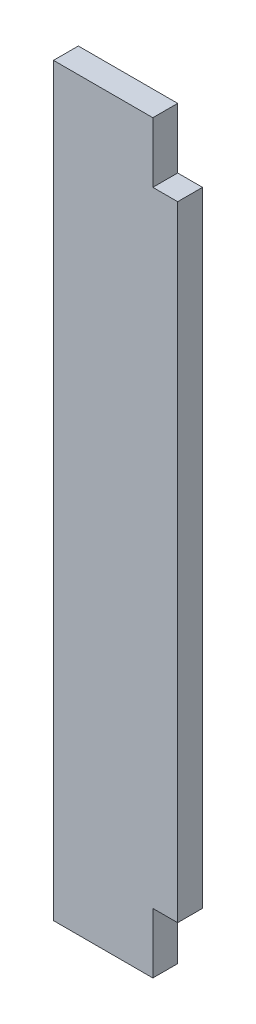
SolidWorks part; units mm, degrees
material "Pine"
ref_plane "Front Plane" through (0, 0, 0) normal (0, 0, 1) x (1, 0, 0)
ref_plane "Top Plane" through (0, 0, 0) normal (0, 1, 0) x (1, 0, 0)
ref_plane "Right Plane" through (0, 0, 0) normal (1, 0, 0) x (0, 0, -1)
sketch "Sketch1" plane through (0, 0, 0) normal (0, 0, 1) x (1, 0, 0)
  line L0 (8932.6508, -5243.5125) -> (10226.1458, -5243.5125)
  line L1 (9086.3208, -4722.0918) -> (10222.9708, -4853.7812)
  line L2 (8914.8708, -6342.0625) -> (10197.5708, -6342.0625)
  line L3 (8914.8708, -5808.6625) -> (10197.5708, -5808.6625)
  line L4 (8919.6333, -5253.0375) -> (10218.2083, -5253.0375)
  line L5 (9134.2633, -4656.1375) -> (9134.2633, -4638.3575)
  line L6 (9091.0833, -4638.3575) -> (9134.2633, -4638.3575)
  line L7 (9091.0833, -4567.2375) -> (9091.0833, -4638.3575)
  line L8 (9134.2633, -4656.1375) -> (9581.3033, -4656.1375)
  line L9 (9091.0833, -4567.2375) -> (9624.4833, -4567.2375)
  line L10 (9581.3033, -4656.1375) -> (9581.3033, -4638.3575)
  line L11 (9581.3033, -4638.3575) -> (9624.4833, -4638.3575)
  line L12 (9624.4833, -4567.2375) -> (9624.4833, -4638.3575)
  line L13 (8932.6508, -5225.7325) -> (9344.9775, -5225.7325)
  line L14 (8932.6508, -5256.2125) -> (8932.6508, -5243.5125)
  line L15 (8911.6958, -5256.2125) -> (8932.6508, -5256.2125)
  line L16 (8914.8708, -4722.0918) -> (9086.3208, -4722.0918)
  line L17 (8911.6958, -4715.5913) -> (8932.6508, -4715.5913)
  line L18 (8914.8708, -6342.0625) -> (8914.8708, -5808.6625)
  line L19 (12082.9917, -4722.0918) -> (10946.3417, -4853.7812)
  line L20 (12236.6617, -5243.5125) -> (10943.1667, -5243.5125)
  line L21 (10951.1042, -5253.0375) -> (12249.6792, -5253.0375)
  line L22 (10838.3917, -5656.2625) -> (11308.2917, -5656.2625)
  line L23 (10838.3917, -5719.7625) -> (11308.2917, -5719.7625)
  line L24 (10838.3917, -5742.5368) -> (11308.2917, -5742.5368)
  line L25 (10806.6417, -6342.0625) -> (11340.0417, -6342.0625)
  line L26 (10803.4667, -6335.7125) -> (11343.2167, -6335.7125)
  line L27 (10803.4667, -6317.9325) -> (11343.2167, -6317.9325)
  line L28 (10943.1667, -5225.7325) -> (11376.4483, -5225.7325)
  line L29 (11506.7292, -4754.5625) -> (10806.6417, -4827.5875)
  line L30 (11506.7292, -4567.2375) -> (11506.7292, -4754.5625)
  line L31 (10806.6417, -4567.2375) -> (10806.6417, -4827.5875)
  line L32 (10806.6417, -4567.2375) -> (11506.7292, -4567.2375)
  line L33 (10235.6708, -6329.3625) -> (10245.1958, -6329.3625)
  line L34 (10245.1958, -6329.3625) -> (10254.7208, -6278.5625)
  line L35 (10302.3458, -6329.3625) -> (10311.8708, -6278.5625)
  line L36 (10302.3458, -6329.3625) -> (10292.8208, -6329.3625)
  line L37 (10245.1958, -5821.3625) -> (10254.7208, -5872.1625)
  line L38 (10235.6708, -5821.3625) -> (10245.1958, -5821.3625)
  line L39 (10292.8208, -5821.3625) -> (10302.3458, -5821.3625)
  line L40 (10302.3458, -5821.3625) -> (10311.8708, -5872.1625)
  line L41 (10235.6708, -5821.3625) -> (10235.6708, -6329.3625)
  line L42 (10254.7208, -5872.1625) -> (10254.7208, -6278.5625)
  line L43 (10311.8708, -5872.1625) -> (10311.8708, -6278.5625)
  line L44 (10292.8208, -5821.3625) -> (10292.8208, -6329.3625)
  line L45 (8932.6508, -5225.7325) -> (8932.6508, -4715.5913)
  line L46 (8911.6958, -4715.5913) -> (8911.6958, -5256.2125)
  line L47 (8914.8708, -5248.275) -> (8914.8708, -4722.0918)
  line L48 (8919.6333, -5253.0375) -> (8914.8708, -5248.275)
  line L49 (8914.8708, -5145.0875) -> (8937.426, -5145.0875)
  line L50 (8914.8708, -5202.2375) -> (8937.426, -5202.2375)
  line L51 (10838.3917, -5656.2625) -> (10838.3917, -5719.7625)
  line L52 (10832.0417, -5736.1868) -> (10856.1717, -5736.1868)
  line L53 (10806.6417, -6342.0625) -> (10806.6417, -5818.7368)
  line L54 (10832.0417, -5649.9125) -> (10856.1717, -5649.9125)
  line L55 (10832.0417, -5726.1125) -> (10856.1717, -5726.1125)
  line L56 (10806.6417, -5818.7368) -> (10833.9015, -5818.7368)
  line L57 (10832.0417, -5806.0442) -> (10851.6815, -5806.0442)
  line L58 (10856.1717, -5801.5541) -> (10856.1717, -5736.1868)
  line L59 (10838.3917, -5814.2467) -> (10838.3917, -5742.5368)
  line L60 (10832.0417, -5806.0442) -> (10832.0417, -5736.1868)
  line L61 (10803.4667, -6317.9325) -> (10803.4667, -6335.7125)
  line L62 (10197.5708, -5808.6625) -> (10197.5708, -6342.0625)
  line L63 (9762.3842, -6348.4125) -> (9762.3842, -5802.3125)
  line L64 (9780.1642, -6348.4125) -> (9762.3842, -6348.4125)
  line L65 (9780.1642, -5802.3125) -> (9780.1642, -6348.4125)
  line L66 (9762.3842, -5802.3125) -> (9780.1642, -5802.3125)
  line L67 (9332.2775, -6348.4125) -> (9332.2775, -5802.3125)
  line L68 (9332.2775, -6348.4125) -> (9350.0575, -6348.4125)
  line L69 (9350.0575, -5802.3125) -> (9350.0575, -6348.4125)
  line L70 (9332.2775, -5802.3125) -> (9350.0575, -5802.3125)
  line L71 (9993.8374, -6061.075) -> (9993.8374, -6045.2418)
  line L72 (9998.5999, -6065.8375) -> (10014.4331, -6065.8375)
  line L73 (9998.5999, -6084.8875) -> (10014.4331, -6084.8875)
  line L74 (9993.8374, -6105.4832) -> (9993.8374, -6089.65)
  line L75 (9974.7874, -6105.4832) -> (9974.7874, -6089.65)
  line L76 (9954.1917, -6084.8875) -> (9970.0249, -6084.8875)
  line L77 (9974.7874, -6061.075) -> (9974.7874, -6045.2418)
  line L78 (9954.1917, -6065.8375) -> (9970.0249, -6065.8375)
  line L79 (10793.9417, -6237.2875) -> (10816.4969, -6237.2875)
  line L80 (10793.9417, -6294.4375) -> (10816.4969, -6294.4375)
  line L81 (10856.1717, -5649.9125) -> (10856.1717, -5726.1125)
  line L82 (10832.0417, -5726.1125) -> (10832.0417, -5649.9125)
  line L83 (10226.1458, -5225.7325) -> (10226.1458, -5243.5125)
  line L84 (10205.1908, -5257.8) -> (10205.1908, -4844.2499)
  line L85 (10230.9083, -4844.2499) -> (10230.9083, -5257.8)
  line L86 (10205.1908, -5257.8) -> (10230.9083, -5257.8)
  line L87 (10205.1908, -4844.2499) -> (10230.9083, -4844.2499)
  line L88 (10946.3417, -5176.8375) -> (10968.8969, -5176.8375)
  line L89 (9349.4676, -5141.9125) -> (9358.2674, -5141.9125)
  line L90 (10946.3417, -5119.6875) -> (10968.8969, -5119.6875)
  line L91 (9929.011, -4660.9635) -> (10066.0807, -4660.9635)
  line L92 (9929.011, -4678.7435) -> (10066.0807, -4678.7435)
  line L93 (10943.1667, -5225.7325) -> (10943.1667, -5243.5125)
  line L94 (10946.3417, -5248.275) -> (10951.1042, -5253.0375)
  line L95 (10946.3417, -5257.8063) -> (10946.3417, -4849.0188)
  line L96 (10964.1217, -5257.8) -> (10964.1217, -4844.2499)
  line L97 (10938.4042, -4844.2499) -> (10938.4042, -5257.8)
  line L98 (10938.4042, -5257.8) -> (10964.1217, -5257.8)
  line L99 (10964.1217, -4844.2499) -> (10938.4042, -4844.2499)
  line L100 (10344.8908, -4560.8875) -> (10369.0208, -4560.8875)
  line L101 (10344.8908, -4560.8875) -> (10369.0208, -4560.8875)
  line L102 (10800.2917, -4560.8875) -> (10824.4217, -4560.8875)
  line L103 (10200.4156, -5119.6875) -> (10222.9708, -5119.6875)
  line L104 (10200.4156, -5176.8375) -> (10222.9708, -5176.8375)
  line L105 (9344.9775, -5146.4026) -> (9344.9775, -5225.7325)
  line L106 (10344.8908, -4560.8875) -> (10344.8908, -4833.9375)
  line L107 (9792.8642, -5225.7325) -> (9792.8642, -5146.4026)
  line L108 (9362.7575, -5225.7325) -> (9775.0842, -5225.7325)
  line L109 (9680.3633, -4761.8396) -> (9680.3633, -4559.9604)
  line L110 (9656.2333, -4559.9604) -> (9680.3633, -4559.9604)
  line L111 (9656.2333, -4761.8396) -> (9680.3633, -4761.8396)
  line L112 (9656.2333, -4761.8396) -> (9656.2333, -4559.9604)
  line L113 (9779.5743, -5141.9125) -> (9788.374, -5141.9125)
  line L114 (10070.5708, -4665.4536) -> (10070.5708, -4674.2534)
  line L115 (9924.5208, -4674.2534) -> (9924.5208, -4665.4536)
  line L116 (12127.4417, -6188.3925) -> (12205.5015, -6188.3925)
  line L117 (12209.9917, -6170.6125) -> (12209.9917, -6183.9024)
  line L118 (9792.8642, -5225.7325) -> (10226.1458, -5225.7325)
  line L119 (9662.5833, -4754.5625) -> (10362.6708, -4827.5875)
  line L120 (9662.5833, -4567.2375) -> (9662.5833, -4754.5625)
  line L121 (10362.6708, -4567.2375) -> (10362.6708, -4827.5875)
  line L122 (9662.5833, -4567.2375) -> (10362.6708, -4567.2375)
  line L123 (10824.4217, -4833.9375) -> (10800.2917, -4833.9375)
  line L124 (10800.2917, -4833.9375) -> (10800.2917, -4560.8875)
  line L125 (10824.4217, -4560.8875) -> (10824.4217, -4833.9375)
  line L126 (10344.8908, -4833.9375) -> (10369.0208, -4833.9375)
  line L127 (10369.0208, -4833.9375) -> (10369.0208, -4560.8875)
  line L128 (10222.9708, -5248.275) -> (10218.2083, -5253.0375)
  line L129 (10222.9708, -5257.8063) -> (10222.9708, -4849.0188)
  line L130 (11734.6544, -5701.375) -> (11739.2301, -5701.375)
  line L131 (9362.7575, -5225.7325) -> (9362.7575, -5146.4026)
  line L132 (9775.0842, -5146.4026) -> (9775.0842, -5225.7325)
  line L133 (11761.3864, -5701.375) -> (11756.8282, -5701.375)
  line L134 (11734.6544, -5693.755) -> (11739.2301, -5693.755)
  line L135 (11761.4039, -5693.755) -> (11756.8282, -5693.755)
  line L136 (11734.6544, -5701.375) -> (11739.2301, -5701.375)
  line L137 (11744.3462, -5721.3024) -> (11744.3462, -5706.4179)
  line L138 (11751.7122, -5721.3024) -> (11751.7122, -5706.4179)
  line L139 (11740.0917, -6170.6125) -> (11740.0917, -6183.9024)
  line L140 (11689.2917, -6188.3925) -> (11822.6417, -6188.3925)
  line L141 (11689.2917, -6348.4093) -> (11689.2917, -6164.2657)
  line L142 (11689.2917, -6164.2657) -> (11746.4417, -6164.2657)
  line L143 (11746.4417, -6164.2657) -> (11746.4417, -6188.3925)
  line L144 (11689.2917, -6164.2657) -> (11746.4417, -6164.2657)
  line L145 (11340.0417, -5818.7368) -> (11340.0417, -6342.0625)
  line L146 (11290.5117, -5726.1125) -> (11314.6417, -5726.1125)
  line L147 (11290.5117, -5649.9125) -> (11290.5117, -5726.1125)
  line L148 (11340.0417, -5818.7368) -> (11312.7818, -5818.7368)
  line L149 (11314.6417, -5806.0442) -> (11295.0018, -5806.0442)
  line L150 (11290.5117, -5801.5541) -> (11290.5117, -5736.1868)
  line L151 (11308.2917, -5814.2467) -> (11308.2917, -5742.5368)
  line L152 (11314.6417, -5806.0442) -> (11314.6417, -5736.1868)
  line L153 (11290.5117, -5736.1868) -> (11314.6417, -5736.1868)
  line L154 (11848.0417, -6267.1325) -> (11962.3417, -6267.1325)
  line L155 (11962.3417, -6267.1325) -> (11962.3417, -6203.6325)
  line L156 (11343.2167, -6317.9325) -> (11343.2167, -6335.7125)
  line L157 (11365.4417, -5656.2625) -> (11365.4417, -5719.7625)
  line L158 (11365.4417, -5656.2625) -> (11479.7417, -5656.2625)
  line L159 (11778.1917, -6071.3937) -> (11802.3217, -6071.3937)
  line L160 (11314.6417, -5726.1125) -> (11314.6417, -5649.9125)
  line L161 (11314.6417, -5649.9125) -> (11290.5117, -5649.9125)
  line L162 (11308.2917, -5719.7625) -> (11308.2917, -5656.2625)
  line L163 (11689.2917, -6348.4093) -> (11713.4217, -6348.4093)
  line L164 (12203.6417, -6164.2657) -> (12260.7917, -6164.2657)
  line L165 (11713.4217, -6348.4093) -> (11713.4217, -6164.2657)
  line L166 (11695.6417, -6342.0625) -> (11695.6417, -6170.6125)
  line L167 (11695.6417, -6048.5337) -> (11699.4517, -6052.3437)
  line L168 (11822.6417, -6292.5325) -> (11822.6417, -6188.3925)
  line L169 (11695.6417, -6342.0625) -> (11695.6417, -6170.6125)
  line L170 (11848.0417, -6203.6325) -> (11962.3417, -6203.6325)
  line L171 (11848.0417, -6203.6325) -> (11848.0417, -6267.1325)
  line L172 (11987.7417, -6267.1325) -> (11987.7417, -6203.6325)
  line L173 (11784.5417, -6077.7437) -> (11784.5417, -6141.2438)
  line L174 (11517.8417, -5656.2625) -> (11632.1417, -5656.2625)
  line L175 (11632.1417, -5656.2625) -> (11632.1417, -5719.7625)
  line L176 (11632.1417, -5719.7625) -> (11517.8417, -5719.7625)
  line L177 (11517.8417, -5719.7625) -> (11517.8417, -5656.2625)
  line L178 (11692.4667, -6028.2137) -> (11692.4667, -6045.9937)
  line L179 (11695.6417, -5979.3188) -> (11718.1969, -5979.3188)
  line L180 (11695.6417, -5922.1687) -> (11718.1969, -5922.1687)
  line L181 (11821.0415, -5722.9375) -> (11821.0415, -5943.6)
  line L182 (11687.7042, -5651.5) -> (11701.9917, -5651.5)
  line L183 (11687.7042, -5651.5) -> (11687.7042, -6055.5251)
  line L184 (11687.7042, -6055.5251) -> (11701.9917, -6055.5251)
  line L185 (11701.9917, -6055.5251) -> (11701.9917, -5651.5)
  line L186 (11695.6417, -6055.2013) -> (11695.6417, -5649.595)
  line L187 (11695.6417, -5656.2625) -> (11695.6417, -6048.5337)
  line L188 (11695.6417, -6170.6125) -> (11740.0917, -6170.6125)
  line L189 (12203.6417, -6164.2657) -> (12203.6417, -6188.3925)
  line L190 (12254.4417, -6342.0625) -> (12254.4417, -6170.6125)
  line L191 (12129.0419, -5943.6) -> (12129.0419, -5722.9375)
  line L192 (12254.4417, -6048.5337) -> (12250.6317, -6052.3437)
  line L193 (12257.6167, -6045.9937) -> (12257.6167, -6028.2137)
  line L194 (12248.0917, -5651.5) -> (12262.3792, -5651.5)
  line L195 (12262.3792, -5651.5) -> (12262.3792, -6055.5251)
  line L196 (12262.3792, -6055.5251) -> (12248.0917, -6055.5251)
  line L197 (12248.0917, -6055.5251) -> (12248.0917, -5651.5)
  line L198 (12254.4417, -6141.2438) -> (12254.4417, -6077.7437)
  line L199 (12236.6617, -6164.2657) -> (12260.7917, -6164.2657)
  line L200 (12102.0417, -6267.1325) -> (11987.7417, -6267.1325)
  line L201 (11330.1865, -6237.2875) -> (11352.7417, -6237.2875)
  line L202 (11330.1865, -6294.4375) -> (11352.7417, -6294.4375)
  line L203 (11474.6617, -5851.8425) -> (11492.4417, -5851.8425)
  line L204 (11474.6617, -5808.6625) -> (11474.6617, -5851.8425)
  line L205 (11403.5417, -5808.6625) -> (11474.6617, -5808.6625)
  line L206 (11492.4417, -5851.8425) -> (11492.4417, -6298.8825)
  line L207 (11403.5417, -6342.0625) -> (11403.5417, -5808.6625)
  line L208 (11474.6617, -6298.8825) -> (11492.4417, -6298.8825)
  line L209 (11474.6617, -6342.0625) -> (11474.6617, -6298.8825)
  line L210 (11403.5417, -6342.0625) -> (11474.6617, -6342.0625)
  line L211 (11619.4417, -5851.8425) -> (11601.6617, -5851.8425)
  line L212 (11601.6617, -5808.6625) -> (11601.6617, -5851.8425)
  line L213 (11530.5417, -5808.6625) -> (11601.6617, -5808.6625)
  line L214 (11619.4417, -5851.8425) -> (11619.4417, -6298.8825)
  line L215 (11530.5417, -6342.0625) -> (11530.5417, -5808.6625)
  line L216 (11619.4417, -6298.8825) -> (11601.6617, -6298.8825)
  line L217 (11601.6617, -6342.0625) -> (11601.6617, -6298.8825)
  line L218 (11530.5417, -6342.0625) -> (11601.6617, -6342.0625)
  line L219 (11479.7417, -5719.7625) -> (11479.7417, -5656.2625)
  line L220 (11365.4417, -5719.7625) -> (11479.7417, -5719.7625)
  line L221 (11778.1917, -6147.5937) -> (11802.3217, -6147.5937)
  line L222 (11802.3217, -6071.3937) -> (11802.3217, -6147.5937)
  line L223 (11778.1917, -6147.5937) -> (11778.1917, -6071.3937)
  line L224 (12254.4417, -5922.1687) -> (12231.8865, -5922.1687)
  line L225 (12254.4417, -5979.3188) -> (12231.8865, -5979.3188)
  line L226 (12254.4417, -6055.2013) -> (12254.4417, -5649.595)
  line L227 (12254.4417, -6048.5337) -> (12254.4417, -5656.2625)
  line L228 (11841.6917, -5702.2873) -> (12108.3917, -5702.2873)
  line L229 (11822.6417, -6292.5325) -> (12127.4417, -6292.5325)
  line L230 (12127.4417, -6292.5325) -> (12127.4417, -6188.3925)
  line L231 (12254.4417, -6170.6125) -> (12209.9917, -6170.6125)
  line L232 (11695.6417, -6342.0625) -> (12254.4417, -6342.0625)
  line L233 (12236.6617, -6348.4093) -> (12260.7917, -6348.4093)
  line L234 (12260.7917, -6348.4093) -> (12260.7917, -6164.2657)
  line L235 (12236.6617, -6348.4093) -> (12236.6617, -6164.2657)
  line L236 (12102.0417, -6203.6325) -> (12102.0417, -6267.1325)
  line L237 (11987.7417, -6203.6325) -> (12102.0417, -6203.6325)
  line L238 (12236.6617, -6147.5937) -> (12236.6617, -6071.3937)
  line L239 (12203.6417, -6188.3925) -> (12260.7917, -6188.3925)
  line L240 (11098.7417, -4665.4536) -> (11098.7417, -4674.2534)
  line L241 (11394.2283, -5146.4026) -> (11394.2283, -5225.7325)
  line L242 (11376.4483, -5225.7325) -> (11376.4483, -5146.4026)
  line L243 (11394.2283, -5225.7325) -> (11806.555, -5225.7325)
  line L244 (11841.6917, -5964.2502) -> (12108.3917, -5964.2502)
  line L245 (12236.6617, -6147.5937) -> (12260.7917, -6147.5937)
  line L246 (12236.6617, -5256.2125) -> (12236.6617, -5243.5125)
  line L247 (12260.7917, -6147.5937) -> (12260.7917, -6071.3937)
  line L248 (12260.7917, -6071.3937) -> (12236.6617, -6071.3937)
  line L249 (12254.4417, -6077.7437) -> (11784.5417, -6077.7437)
  line L250 (11784.5417, -6141.2438) -> (12254.4417, -6141.2438)
  line L252 (12254.4417, -5656.2625) -> (11695.6417, -5656.2625)
  line L253 (11699.4517, -6052.3437) -> (12250.6317, -6052.3437)
  line L254 (11692.4667, -6045.9937) -> (12257.6167, -6045.9937)
  line L255 (11692.4667, -6028.2137) -> (12257.6167, -6028.2137)
  line L256 (11824.335, -5146.4026) -> (11824.335, -5225.7325)
  line L257 (11811.0451, -5141.9125) -> (11819.8449, -5141.9125)
  line L258 (11244.7917, -4674.2534) -> (11244.7917, -4665.4536)
  line L259 (11806.555, -5225.7325) -> (11806.555, -5146.4026)
  line L260 (11488.9492, -4761.8396) -> (11488.9492, -4559.9604)
  line L261 (11488.9492, -4559.9604) -> (11513.0792, -4559.9604)
  line L262 (11488.9492, -4761.8396) -> (11513.0792, -4761.8396)
  line L263 (11513.0792, -4761.8396) -> (11513.0792, -4559.9604)
  line L264 (11240.3015, -4660.9635) -> (11103.2318, -4660.9635)
  line L265 (11103.2318, -4678.7435) -> (11240.3015, -4678.7435)
  line L266 (12236.6617, -5225.7325) -> (12236.6617, -4715.5913)
  line L267 (12257.6167, -4715.5913) -> (12257.6167, -5256.2125)
  line L268 (12254.4417, -5248.275) -> (12254.4417, -4722.0918)
  line L269 (12236.6617, -5225.7325) -> (11824.335, -5225.7325)
  line L270 (12035.0492, -4656.1375) -> (12035.0492, -4638.3575)
  line L271 (12078.2292, -4638.3575) -> (12035.0492, -4638.3575)
  line L272 (12078.2292, -4567.2375) -> (12078.2292, -4638.3575)
  line L273 (12035.0492, -4656.1375) -> (11588.0092, -4656.1375)
  line L274 (11544.8292, -4567.2375) -> (12078.2292, -4567.2375)
  line L275 (11588.0092, -4656.1375) -> (11588.0092, -4638.3575)
  line L276 (11544.8292, -4638.3575) -> (11588.0092, -4638.3575)
  line L277 (11544.8292, -4567.2375) -> (11544.8292, -4638.3575)
  line L278 (12249.6792, -5253.0375) -> (12254.4417, -5248.275)
  line L280 (12257.6167, -5256.2125) -> (12236.6617, -5256.2125)
  line L281 (12231.8865, -5145.0875) -> (12254.4417, -5145.0875)
  line L282 (12231.8865, -5202.2375) -> (12254.4417, -5202.2375)
  line L283 (12236.6617, -4715.5913) -> (12257.6167, -4715.5913)
  line L284 (12082.9917, -4722.0918) -> (12254.4417, -4722.0918)
  line L285 (11380.9385, -5141.9125) -> (11389.7382, -5141.9125)
  circle A0 centre (8923.7608, -4778.9042) radius 1.5875
  circle A1 centre (9062.6598, -4736.3765) radius 2.3685
  circle A2 centre (9051.3958, -6281.7375) radius 22.225
  circle A3 centre (9083.1458, -6249.9875) radius 1.5875
  circle A4 centre (9083.1458, -6313.4875) radius 1.5875
  circle A5 centre (9019.6458, -6249.9875) radius 1.5875
  circle A6 centre (9019.6458, -6313.4875) radius 1.5875
  circle A7 centre (8972.3383, -5202.2375) radius 1.5875
  circle A8 centre (8923.7608, -5015.9708) radius 1.5875
  circle A9 centre (8923.7608, -5134.5042) radius 1.5875
  circle A10 centre (9054.5708, -5234.6225) radius 1.5875
  circle A11 centre (8923.7608, -4897.4375) radius 1.5875
  circle A12 centre (8972.3383, -5087.9375) radius 1.5875
  circle A13 centre (8972.3383, -5145.0875) radius 1.5875
  circle A14 centre (10847.2817, -5668.9625) radius 1.5875
  circle A15 centre (10847.2817, -5707.0625) radius 1.5875
  circle A16 centre (10847.2817, -5755.2368) radius 1.5875
  circle A17 centre (10851.4092, -6237.2875) radius 1.5875
  circle A18 centre (10851.4092, -6294.4375) radius 1.5875
  circle A19 centre (10847.2817, -5793.3442) radius 1.5875
  arc A20 (10833.9015, -5818.7368) -> (10838.3917, -5814.2467) centre (10836.1466, -5816.4918) ccw
  arc A21 (10851.6815, -5806.0442) -> (10856.1717, -5801.5541) centre (10853.9266, -5803.7992) ccw
  circle A22 centre (10882.8417, -6040.4375) radius 1.5875
  circle A23 centre (10882.8417, -6218.2375) radius 1.5875
  circle A24 centre (10882.8417, -5862.6375) radius 1.5875
  circle A25 centre (10908.2417, -6326.8225) radius 1.5875
  circle A26 centre (10908.2417, -6326.8225) radius 1.5875
  circle A27 centre (10851.4092, -6180.1375) radius 1.5875
  circle A28 centre (10815.5317, -4783.4231) radius 1.5875
  circle A29 centre (10815.5317, -4696.9488) radius 1.5875
  circle A30 centre (10815.5317, -4610.4746) radius 1.5875
  circle A31 centre (10979.1323, -4867.0082) radius 2.3685
  circle A32 centre (10190.1802, -4867.0082) radius 2.3685
  circle A33 centre (10955.2317, -4929.9812) radius 1.5875
  circle A34 centre (10955.2317, -5031.5812) radius 1.5875
  circle A35 centre (10214.0808, -4929.9812) radius 1.5875
  circle A36 centre (10214.0808, -5031.5812) radius 1.5875
  circle A37 centre (9341.1675, -6265.8625) radius 1.5875
  circle A38 centre (9771.2742, -5884.8625) radius 1.5875
  circle A39 centre (9771.2742, -6138.8625) radius 1.5875
  circle A40 centre (9771.2742, -6011.8625) radius 1.5875
  arc A41 (10036.2287, -6113.8083) -> (10051.3426, -6111.6033) centre (10042.9639, -6107.0732) ccw
  arc A42 (10051.3426, -6111.6033) -> (10051.3426, -6039.1217) centre (9984.3124, -6075.3625) ccw
  arc A43 (10051.3426, -6039.1217) -> (10036.2287, -6036.9167) centre (10042.9639, -6043.6518) ccw
  arc A44 (10034.5851, -6102.5431) -> (10034.5851, -6048.1819) centre (9984.3124, -6075.3625) ccw
  arc A45 (10034.5851, -6102.5431) -> (10036.2287, -6113.8083) centre (10042.9639, -6107.0732) ccw
  arc A46 (10036.2287, -6036.9167) -> (10034.5851, -6048.1819) centre (10042.9639, -6043.6518) ccw
  arc A47 (9945.8666, -6127.2787) -> (9948.0717, -6142.3927) centre (9952.6018, -6134.0139) ccw
  arc A48 (9948.0717, -6142.3927) -> (10020.5532, -6142.3927) centre (9984.3124, -6075.3625) ccw
  arc A49 (10020.5532, -6142.3927) -> (10022.7583, -6127.2787) centre (10016.0231, -6134.0139) ccw
  arc A50 (9957.1319, -6125.6352) -> (10011.493, -6125.6352) centre (9984.3124, -6075.3625) ccw
  arc A51 (9957.1319, -6125.6352) -> (9945.8666, -6127.2787) centre (9952.6018, -6134.0139) ccw
  arc A52 (10022.7583, -6127.2787) -> (10011.493, -6125.6352) centre (10016.0231, -6134.0139) ccw
  arc A53 (9932.3962, -6036.9167) -> (9917.2822, -6039.1217) centre (9925.661, -6043.6518) ccw
  arc A54 (9917.2822, -6039.1217) -> (9917.2822, -6111.6033) centre (9984.3124, -6075.3625) ccw
  arc A55 (9917.2822, -6111.6033) -> (9932.3962, -6113.8083) centre (9925.661, -6107.0732) ccw
  arc A56 (9934.0398, -6048.1819) -> (9934.0398, -6102.5431) centre (9984.3124, -6075.3625) ccw
  arc A57 (9934.0398, -6048.1819) -> (9932.3962, -6036.9167) centre (9925.661, -6043.6518) ccw
  arc A58 (9932.3962, -6113.8083) -> (9934.0398, -6102.5431) centre (9925.661, -6107.0732) ccw
  arc A59 (9945.8666, -6023.4463) -> (9957.1319, -6025.0898) centre (9952.6018, -6016.7111) ccw
  arc A60 (10011.493, -6025.0898) -> (10022.7583, -6023.4463) centre (10016.0231, -6016.7111) ccw
  arc A61 (10011.493, -6025.0898) -> (9957.1319, -6025.0898) centre (9984.3124, -6075.3625) ccw
  arc A62 (9948.0717, -6008.3323) -> (9945.8666, -6023.4463) centre (9952.6018, -6016.7111) ccw
  arc A63 (10020.5532, -6008.3323) -> (9948.0717, -6008.3323) centre (9984.3124, -6075.3625) ccw
  arc A64 (10022.7583, -6023.4463) -> (10020.5532, -6008.3323) centre (10016.0231, -6016.7111) ccw
  arc A65 (10005.0943, -6187.7574) -> (10096.7073, -6096.1443) centre (9984.3124, -6075.3625) ccw
  arc A66 (9993.8374, -6178.3911) -> (10005.0943, -6187.7574) centre (10003.3624, -6178.3911) ccw
  arc A67 (10001.6306, -6169.0249) -> (10077.9748, -6092.6807) centre (9984.3124, -6075.3625) ccw
  arc A68 (10087.3411, -6084.8875) -> (10077.9748, -6092.6807) centre (10087.3411, -6094.4125) ccw
  arc A69 (10001.6306, -6169.0249) -> (9993.8374, -6178.3911) centre (10003.3624, -6178.3911) ccw
  arc A70 (9963.5306, -6187.7574) -> (9974.7874, -6178.3911) centre (9965.2624, -6178.3911) ccw
  arc A71 (9871.9176, -6096.1443) -> (9963.5306, -6187.7574) centre (9984.3124, -6075.3625) ccw
  arc A72 (9881.2838, -6084.8875) -> (9871.9176, -6096.1443) centre (9881.2838, -6094.4125) ccw
  arc A73 (9890.65, -6092.6807) -> (9966.9943, -6169.0249) centre (9984.3124, -6075.3625) ccw
  arc A74 (9974.7874, -6178.3911) -> (9966.9943, -6169.0249) centre (9965.2624, -6178.3911) ccw
  arc A75 (9890.65, -6092.6807) -> (9881.2838, -6084.8875) centre (9881.2838, -6094.4125) ccw
  arc A76 (9871.9176, -6054.5807) -> (9881.2838, -6065.8375) centre (9881.2838, -6056.3125) ccw
  arc A77 (9963.5306, -5962.9676) -> (9871.9176, -6054.5807) centre (9984.3124, -6075.3625) ccw
  arc A78 (9974.7874, -5972.3339) -> (9963.5306, -5962.9676) centre (9965.2624, -5972.3339) ccw
  arc A79 (9966.9943, -5981.7001) -> (9890.65, -6058.0443) centre (9984.3124, -6075.3625) ccw
  arc A80 (9881.2838, -6065.8375) -> (9890.65, -6058.0443) centre (9881.2838, -6056.3125) ccw
  arc A81 (9966.9943, -5981.7001) -> (9974.7874, -5972.3339) centre (9965.2624, -5972.3339) ccw
  arc A82 (10077.9748, -6058.0443) -> (10087.3411, -6065.8375) centre (10087.3411, -6056.3125) ccw
  arc A83 (9993.8374, -5972.3339) -> (10001.6306, -5981.7001) centre (10003.3624, -5972.3339) ccw
  arc A84 (10077.9748, -6058.0443) -> (10001.6306, -5981.7001) centre (9984.3124, -6075.3625) ccw
  arc A85 (10087.3411, -6065.8375) -> (10096.7073, -6054.5807) centre (10087.3411, -6056.3125) ccw
  arc A86 (10096.7073, -6054.5807) -> (10005.0943, -5962.9676) centre (9984.3124, -6075.3625) ccw
  arc A87 (10005.0943, -5962.9676) -> (9993.8374, -5972.3339) centre (10003.3624, -5972.3339) ccw
  arc A88 (10014.4331, -6065.8375) -> (10018.7361, -6059.0339) centre (10014.4331, -6061.075) ccw
  arc A89 (10018.7361, -6059.0339) -> (10000.641, -6040.9388) centre (9984.3124, -6075.3625) ccw
  arc A90 (10000.641, -6040.9388) -> (9993.8374, -6045.2418) centre (9998.5999, -6045.2418) ccw
  arc A91 (9993.8374, -6061.075) -> (9998.5999, -6065.8375) centre (9998.5999, -6061.075) ccw
  arc A92 (9993.8374, -6105.4832) -> (10000.641, -6109.7862) centre (9998.5999, -6105.4832) ccw
  arc A93 (10000.641, -6109.7862) -> (10018.7361, -6091.6911) centre (9984.3124, -6075.3625) ccw
  arc A94 (10018.7361, -6091.6911) -> (10014.4331, -6084.8875) centre (10014.4331, -6089.65) ccw
  arc A95 (9998.5999, -6084.8875) -> (9993.8374, -6089.65) centre (9998.5999, -6089.65) ccw
  arc A96 (9954.1917, -6084.8875) -> (9949.8888, -6091.6911) centre (9954.1917, -6089.65) ccw
  arc A97 (9949.8888, -6091.6911) -> (9967.9839, -6109.7862) centre (9984.3124, -6075.3625) ccw
  arc A98 (9967.9839, -6109.7862) -> (9974.7874, -6105.4832) centre (9970.0249, -6105.4832) ccw
  arc A99 (9974.7874, -6089.65) -> (9970.0249, -6084.8875) centre (9970.0249, -6089.65) ccw
  arc A100 (9970.0249, -6065.8375) -> (9974.7874, -6061.075) centre (9970.0249, -6061.075) ccw
  arc A101 (9949.8888, -6059.0339) -> (9954.1917, -6065.8375) centre (9954.1917, -6061.075) ccw
  arc A102 (9967.9839, -6040.9388) -> (9949.8888, -6059.0339) centre (9984.3124, -6075.3625) ccw
  arc A103 (9974.7874, -6045.2418) -> (9967.9839, -6040.9388) centre (9970.0249, -6045.2418) ccw
  arc A104 (10096.7073, -6096.1443) -> (10087.3411, -6084.8875) centre (10087.3411, -6094.4125) ccw
  circle A105 centre (9771.2742, -6265.8625) radius 1.5875
  circle A106 centre (9341.1675, -5884.8625) radius 1.5875
  circle A107 centre (9341.1675, -6138.8625) radius 1.5875
  circle A108 centre (9341.1675, -6011.8625) radius 1.5875
  circle A109 centre (11037.2315, -4887.5494) radius 15.0812
  arc A110 (9349.4676, -5141.9125) -> (9344.9775, -5146.4026) centre (9347.2226, -5144.1576) ccw
  arc A111 (9362.7575, -5146.4026) -> (9358.2674, -5141.9125) centre (9360.5124, -5144.1576) ccw
  circle A112 centre (9946.7458, -4669.8535) radius 1.5875
  arc A113 (9924.5208, -4674.2534) -> (9929.011, -4678.7435) centre (9926.7659, -4676.4984) ccw
  circle A114 centre (11003.8092, -5176.8375) radius 1.5875
  circle A115 centre (11003.8092, -5119.6875) radius 1.5875
  circle A116 centre (10353.7808, -4696.9488) radius 1.5875
  circle A117 centre (10353.7808, -4610.4746) radius 1.5875
  circle A118 centre (10353.7808, -4783.4231) radius 1.5875
  circle A119 centre (11003.8092, -5062.5375) radius 1.5875
  circle A120 centre (9353.8675, -5160.9625) radius 1.5875
  circle A121 centre (9638.7708, -5234.6225) radius 1.5875
  circle A122 centre (9671.4733, -4724.1144) radius 1.5875
  circle A123 centre (9671.4733, -4661.3637) radius 1.5875
  circle A124 centre (9671.4733, -4598.6129) radius 1.5875
  arc A125 (9792.8642, -5146.4026) -> (9788.374, -5141.9125) centre (9790.6191, -5144.1576) ccw
  arc A126 (9779.5743, -5141.9125) -> (9775.0842, -5146.4026) centre (9777.3292, -5144.1576) ccw
  circle A127 centre (10048.3458, -4669.8535) radius 1.5875
  arc A128 (10070.5708, -4665.4536) -> (10066.0807, -4660.9635) centre (10068.3258, -4663.2086) ccw
  arc A129 (10066.0807, -4678.7435) -> (10070.5708, -4674.2534) centre (10068.3258, -4676.4984) ccw
  circle A130 centre (9997.5458, -4669.8535) radius 1.5875
  arc A131 (9929.011, -4660.9635) -> (9924.5208, -4665.4536) centre (9926.7659, -4663.2086) ccw
  circle A132 centre (10132.081, -4887.5494) radius 15.0812
  circle A133 centre (10165.5033, -5176.8375) radius 1.5875
  circle A134 centre (10165.5033, -5119.6875) radius 1.5875
  circle A135 centre (9486.3708, -5234.6225) radius 1.5875
  circle A136 centre (10165.5033, -5062.5375) radius 1.5875
  circle A137 centre (9206.9708, -5234.6225) radius 1.5875
  circle A138 centre (10070.5708, -5234.6225) radius 1.5875
  circle A139 centre (9918.1708, -5234.6225) radius 1.5875
  circle A140 centre (9783.9742, -5160.9625) radius 1.5875
  circle A141 centre (9783.9742, -5193.9825) radius 1.5875
  circle A142 centre (9353.8675, -5193.9825) radius 1.5875
  circle A143 centre (11073.3417, -6326.8225) radius 1.5875
  circle A144 centre (11073.3417, -6326.8225) radius 1.5875
  circle A145 centre (11295.2742, -6180.1375) radius 1.5875
  circle A146 centre (11295.2742, -6294.4375) radius 1.5875
  circle A147 centre (11295.2742, -6237.2875) radius 1.5875
  circle A148 centre (11975.0417, -5692.775) radius 3.4925
  circle A149 centre (11263.8417, -5862.6375) radius 1.5875
  arc A150 (11739.2301, -5701.375) -> (11744.3462, -5706.4179) centre (11748.0292, -5697.565) ccw
  arc A151 (11751.7122, -5706.4179) -> (11756.8282, -5701.375) centre (11748.0292, -5697.565) ccw
  arc A152 (11744.3462, -5721.3024) -> (11751.7122, -5721.3024) centre (11748.0292, -5725.505) ccw
  arc A153 (11734.6544, -5693.755) -> (11724.9787, -5697.565) centre (11730.5667, -5697.565) ccw
  arc A154 (11756.8282, -5693.755) -> (11739.2301, -5693.755) centre (11748.0292, -5697.565) ccw
  arc A155 (11724.9787, -5697.565) -> (11734.6544, -5701.375) centre (11730.5667, -5697.565) ccw
  arc A156 (11761.3864, -5701.375) -> (11771.0797, -5697.565) centre (11765.4842, -5697.565) ccw
  arc A157 (11771.0797, -5697.565) -> (11761.4039, -5693.755) centre (11765.4917, -5697.565) ccw
  arc A158 (11740.0917, -6183.9024) -> (11744.5818, -6188.3925) centre (11742.3367, -6186.1474) ccw
  arc A159 (12205.5015, -6188.3925) -> (12209.9917, -6183.9024) centre (12207.7466, -6186.1474) ccw
  circle A160 centre (11299.4017, -5793.3442) radius 1.5875
  arc A161 (11308.2917, -5814.2467) -> (11312.7818, -5818.7368) centre (11310.5367, -5816.4918) ccw
  arc A162 (11290.5117, -5801.5541) -> (11295.0018, -5806.0442) centre (11292.7567, -5803.7992) ccw
  circle A163 centre (11704.5317, -6314.149) radius 1.5875
  circle A164 centre (11748.9817, -6208.7125) radius 1.5875
  circle A165 centre (11263.8417, -6218.2375) radius 1.5875
  circle A166 centre (11263.8417, -6040.4375) radius 1.5875
  circle A167 centre (11238.4417, -6326.8225) radius 1.5875
  circle A168 centre (11238.4417, -6326.8225) radius 1.5875
  circle A169 centre (11299.4017, -5668.9625) radius 1.5875
  circle A170 centre (11299.4017, -5707.0625) radius 1.5875
  circle A171 centre (11726.7567, -6179.5025) radius 1.5875
  circle A172 centre (11704.5317, -6199.3198) radius 1.5875
  circle A173 centre (11748.9817, -6272.2125) radius 1.5875
  circle A174 centre (11704.5317, -6256.7344) radius 1.5875
  circle A175 centre (11299.4017, -5755.2368) radius 1.5875
  circle A176 centre (11913.4467, -6301.4225) radius 1.5875
  circle A177 centre (11790.2567, -6301.4225) radius 1.5875
  circle A178 centre (11793.4317, -6128.5437) radius 1.5875
  circle A179 centre (11753.1092, -5865.0188) radius 1.5875
  circle A180 centre (11809.9417, -6037.1038) radius 1.5875
  circle A181 centre (11809.9417, -6037.1038) radius 1.5875
  circle A182 centre (11753.1092, -5922.1687) radius 1.5875
  circle A183 centre (11975.0417, -5973.7625) radius 3.4925
  circle A184 centre (11975.0417, -6037.1038) radius 1.5875
  circle A185 centre (11753.1092, -5979.3188) radius 1.5875
  circle A186 centre (11975.0417, -6037.1038) radius 1.5875
  arc A187 (11841.6917, -5702.2873) -> (11821.0415, -5722.9375) centre (11841.6917, -5722.9375) ccw
  circle A188 centre (11811.5292, -5833.2687) radius 3.4925
  arc A189 (11821.0415, -5943.6) -> (11841.6917, -5964.2502) centre (11841.6917, -5943.6) ccw
  circle A190 centre (12196.9742, -5865.0188) radius 1.5875
  arc A191 (12129.0419, -5722.9375) -> (12108.3917, -5702.2873) centre (12108.3917, -5722.9375) ccw
  circle A192 centre (12036.6367, -6301.4225) radius 1.5875
  circle A193 centre (12159.8267, -6301.4225) radius 1.5875
  circle A194 centre (12138.5542, -5833.2687) radius 3.4925
  circle A195 centre (12197.2917, -5761.0375) radius 15.0812
  circle A196 centre (11793.4317, -6090.4437) radius 1.5875
  circle A197 centre (12196.9742, -5922.1687) radius 1.5875
  arc A198 (12108.3917, -5964.2502) -> (12129.0419, -5943.6) centre (12108.3917, -5943.6) ccw
  circle A199 centre (12196.9742, -5979.3188) radius 1.5875
  circle A200 centre (12201.1017, -6272.2125) radius 1.5875
  circle A201 centre (12245.5517, -6314.149) radius 1.5875
  circle A202 centre (12245.5517, -6256.7344) radius 1.5875
  circle A203 centre (12201.1017, -6208.7125) radius 1.5875
  circle A204 centre (12223.3267, -6179.5025) radius 1.5875
  circle A205 centre (12245.5517, -6199.3198) radius 1.5875
  circle A206 centre (11171.7667, -4669.8535) radius 1.5875
  circle A207 centre (11222.5667, -4669.8535) radius 1.5875
  arc A208 (11240.3015, -4678.7435) -> (11244.7917, -4674.2534) centre (11242.5466, -4676.4984) ccw
  circle A209 centre (11385.3383, -5193.9825) radius 1.5875
  circle A210 centre (12106.6527, -4736.3765) radius 2.3685
  circle A211 centre (12140.1417, -6037.1038) radius 1.5875
  circle A212 centre (12140.1417, -6037.1038) radius 1.5875
  circle A213 centre (12245.5517, -6090.4437) radius 1.5875
  circle A214 centre (12245.5517, -6128.5437) radius 1.5875
  circle A215 centre (11385.3383, -5160.9625) radius 1.5875
  arc A216 (11824.335, -5146.4026) -> (11819.8449, -5141.9125) centre (11822.0899, -5144.1576) ccw
  arc A217 (11811.0451, -5141.9125) -> (11806.555, -5146.4026) centre (11808.8001, -5144.1576) ccw
  circle A218 centre (11815.445, -5193.9825) radius 1.5875
  circle A219 centre (11815.445, -5160.9625) radius 1.5875
  circle A220 centre (11530.5417, -5234.6225) radius 1.5875
  circle A221 centre (11962.3417, -5234.6225) radius 1.5875
  arc A222 (11244.7917, -4665.4536) -> (11240.3015, -4660.9635) centre (11242.5466, -4663.2086) ccw
  circle A223 centre (11682.9417, -5234.6225) radius 1.5875
  circle A224 centre (11497.8392, -4724.1144) radius 1.5875
  circle A225 centre (11497.8392, -4661.3637) radius 1.5875
  circle A226 centre (11497.8392, -4598.6129) radius 1.5875
  circle A227 centre (11120.9667, -4669.8535) radius 1.5875
  arc A228 (11103.2318, -4660.9635) -> (11098.7417, -4665.4536) centre (11100.9867, -4663.2086) ccw
  arc A229 (11098.7417, -4674.2534) -> (11103.2318, -4678.7435) centre (11100.9867, -4676.4984) ccw
  circle A230 centre (12196.9742, -5202.2375) radius 1.5875
  circle A231 centre (12245.5517, -5015.9708) radius 1.5875
  circle A232 centre (12245.5517, -5134.5042) radius 1.5875
  circle A233 centre (12114.7417, -5234.6225) radius 1.5875
  circle A234 centre (12245.5517, -4897.4375) radius 1.5875
  circle A235 centre (12245.5517, -4778.9042) radius 1.5875
  circle A236 centre (12196.9742, -5087.9375) radius 1.5875
  circle A237 centre (12196.9742, -5145.0875) radius 1.5875
  circle A238 centre (11098.7417, -5234.6225) radius 1.5875
  circle A239 centre (11251.1417, -5234.6225) radius 1.5875
  arc A240 (11380.9385, -5141.9125) -> (11376.4483, -5146.4026) centre (11378.6934, -5144.1576) ccw
  arc A241 (11394.2283, -5146.4026) -> (11389.7382, -5141.9125) centre (11391.9833, -5144.1576) ccw
sketch "Sketch2" plane through (0, 0, 0) normal (0, 0, 1) x (1, 0, 0)
  line L0 (11403.5417, -6342.0625) -> (11474.6617, -6342.0625)
  line L1 (11474.6617, -6342.0625) -> (11474.6617, -6298.8825)
  line L2 (11474.6617, -6298.8825) -> (11492.4417, -6298.8825)
  line L3 (11492.4417, -6298.8825) -> (11492.4417, -5851.8425)
  line L4 (11492.4417, -5851.8425) -> (11474.6617, -5851.8425)
  line L5 (11474.6617, -5851.8425) -> (11474.6617, -5808.6625)
  line L6 (11474.6617, -5808.6625) -> (11403.5417, -5808.6625)
  line L7 (11403.5417, -5808.6625) -> (11403.5417, -6342.0625)
  dimension "D1" = 533.4
  dimension "D2" = 43.18
extrude "Extrude1" add sketch "Sketch2" against normal blind 17.78
